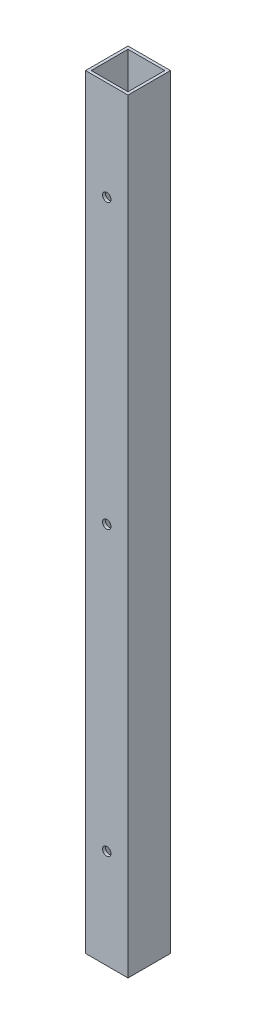
SolidWorks part; units mm, degrees
material "6061-O (SS)"
ref_plane "前视基准面" through (0, 0, 0) normal (0, 0, 1) x (1, 0, 0)
ref_plane "上视基准面" through (0, 0, 0) normal (0, 1, 0) x (1, 0, 0)
ref_plane "右视基准面" through (0, 0, 0) normal (1, 0, 0) x (0, 0, -1)
sketch "草图1" plane through (0, 0, 0) normal (0, 1, 0) x (1, 0, 0)
  line L0 (-6.5, 6.5) -> (6.5, 6.5)
  line L1 (-7.5, -7.5) -> (7.5, -7.5)
  line L2 (-7.5, -7.5) -> (-7.5, 7.5)
  line L3 (-7.5, 7.5) -> (7.5, 7.5)
  line L4 (7.5, -7.5) -> (7.5, 7.5)
  line L5 (-7.5, -7.5) -> (7.5, 7.5) construction
  line L6 (-7.5, 7.5) -> (7.5, -7.5) construction
  line L7 (6.5, -6.5) -> (6.5, 6.5)
  line L8 (-6.5, -6.5) -> (6.5, -6.5)
  line L9 (-6.5, -6.5) -> (-6.5, 6.5)
  point P0 (0, 0)
  dimension "D1" = 15
  dimension "D2" = 1
extrude "凸台-拉伸1" add sketch "草图1" along normal blind 270
sketch "草图2" plane through (0, 0, 7.5) normal (0, 0, 1) x (1, 0, 0)
  line L0 (0, 270) -> (0, 0) construction
  line L1 (-7.5, 270) -> (7.5, 270) construction
  line L2 (-7.5, 135) -> (7.5, 135) construction
  line L3 (-7.5, 270) -> (-7.5, 0) construction
  line L4 (7.5, 270) -> (7.5, 0) construction
  circle A0 centre (0, 235) radius 1.5
  circle A1 centre (0, 35) radius 1.5
  circle A2 centre (0, 135) radius 1.5
  dimension "D1" = 3
  dimension "D3" = 3
  dimension "D2" = 200
extrude "切除-拉伸1" cut sketch "草图2" against normal through all
